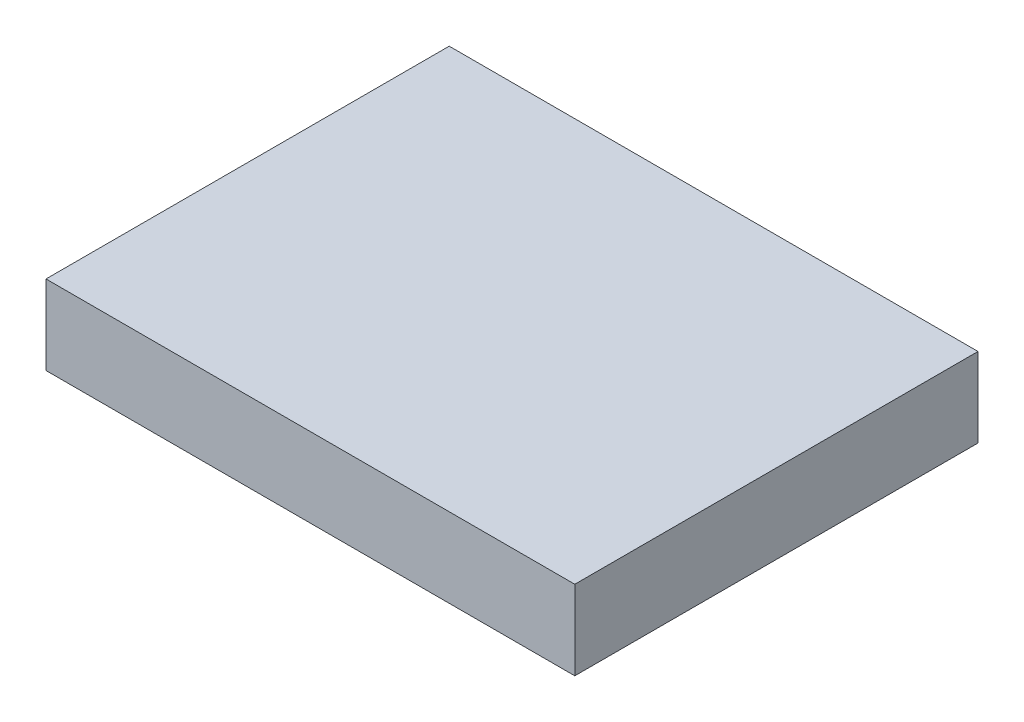
SolidWorks part; units mm, degrees
ref_plane "Front Plane" through (0, 0, 0) normal (0, 0, 1) x (1, 0, 0)
ref_plane "Top Plane" through (0, 0, 0) normal (0, 1, 0) x (1, 0, 0)
ref_plane "Right Plane" through (0, 0, 0) normal (1, 0, 0) x (0, 0, -1)
sketch "Sketch2" plane through (0, 0, 0) normal (0, 1, 0) x (1, 0, 0)
  line L1 (40, -30.5) -> (-40, -30.5)
  line L2 (40, -30.5) -> (40, 30.5)
  line L3 (40, 30.5) -> (-40, 30.5)
  line L4 (-40, -30.5) -> (-40, 30.5)
  line L5 (40, -30.5) -> (-40, 30.5) construction
  line L6 (40, 30.5) -> (-40, -30.5) construction
  point P0 (0, 0)
  dimension "D1" = 80
  dimension "D2" = 61
extrude "Boss-Extrude1" add sketch "Sketch2" along normal blind 12
